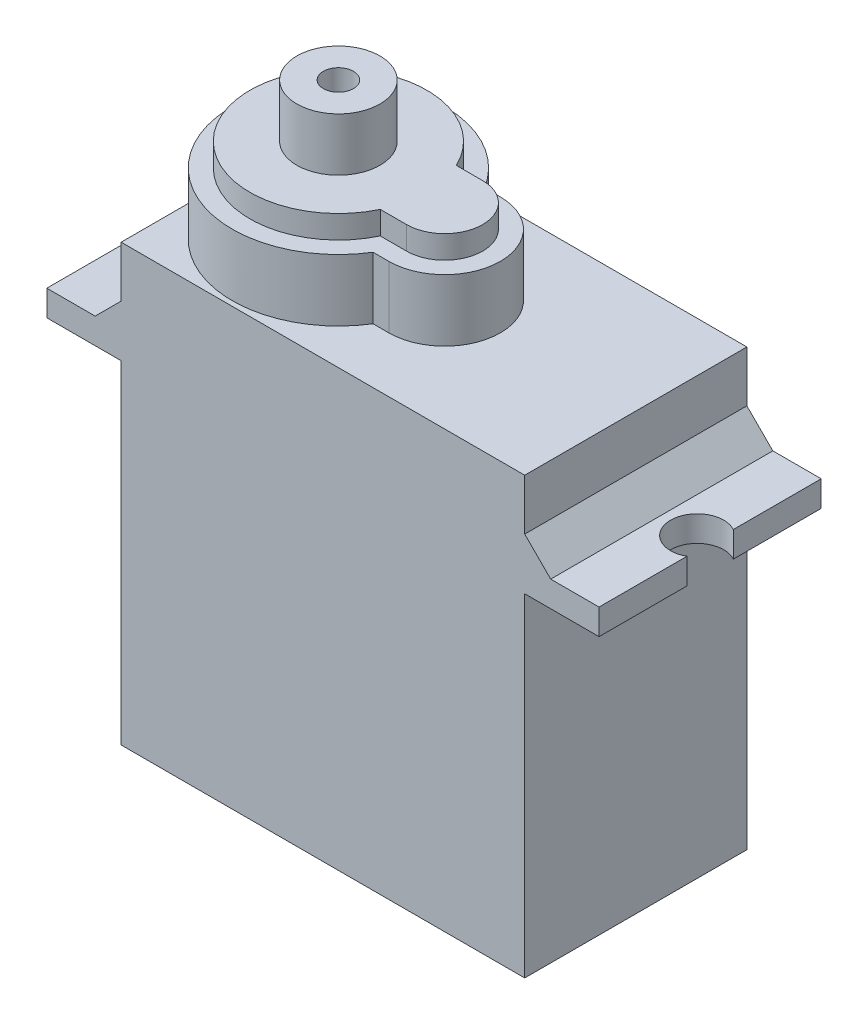
SolidWorks part; units mm, degrees
ref_plane "Piano frontale" through (0, 0, 0) normal (0, 0, 1) x (1, 0, 0)
ref_plane "Piano superiore" through (0, 0, 0) normal (0, 1, 0) x (1, 0, 0)
ref_plane "Piano destro" through (0, 0, 0) normal (1, 0, 0) x (0, 0, -1)
sketch "Schizzo1" plane through (0, 0, 0) normal (0, 0, 1) x (1, 0, 0)
  line L0 (11.4, 21.7179) -> (12.8679, 20.25)
  line L2 (-11.4, 18.8) -> (-11.4, 0)
  line L3 (-11.4, 0) -> (11.4, 0)
  line L4 (11.4, 18.8) -> (11.4, 0)
  line L5 (-15.6, 20.25) -> (-12.8679, 20.25)
  line L6 (-15.6, 20.25) -> (-15.6, 18.8)
  line L7 (-15.6, 18.8) -> (-11.4, 18.8)
  line L8 (15.6, 20.25) -> (15.6, 18.8)
  line L9 (-11.4, 24.6) -> (11.4, 24.6)
  line L10 (-11.4, 24.6) -> (-11.4, 21.7179)
  line L12 (11.4, 24.6) -> (11.4, 21.7179)
  line L13 (12.8679, 20.25) -> (15.6, 20.25)
  line L14 (-11.4, 21.7179) -> (-12.8679, 20.25)
  line L15 (11.4, 18.8) -> (15.6, 18.8)
  dimension "D1" = 18.8
  dimension "D2" = 22.8
  dimension "D3" = 31.2
  dimension "D4" = 1.45
extrude "Estrusione-Estrusione2" add sketch "Schizzo1" along normal blind 12.55
sketch "Schizzo2" plane through (0, 24.6, 0) normal (0, 1, 0) x (1, 0, 0)
  line L0 (-11.4, -12.55) -> (-11.4, 0) construction
  line L1 (0.6, -3.125) -> (-0.2934, -3.125)
  line L2 (0.6, -9.425) -> (-0.2934, -9.425)
  arc A0 (-0.2934, -3.125) -> (-0.2934, -9.425) centre (-5.4, -6.275) ccw
  arc A1 (0.6, -9.425) -> (0.6, -3.125) centre (0.6, -6.275) ccw
  point P2 (-11.4, -6.275)
  dimension "D1" = 12
  dimension "D2" = 6.3
  dimension "D3" = 6
extrude "Estrusione-Estrusione3" add sketch "Schizzo2" along normal blind 3.5
sketch "Schizzo3" plane through (0, 28.1, 0) normal (0, 1, 0) x (1, 0, 0)
  line L0 (-0.8859, -8.425) -> (0.6, -8.425)
  line L1 (0.6, -4.125) -> (-0.8859, -4.125)
  line L2 (-0.2934, -9.425) -> (0.6, -9.425)
  line L3 (0.6, -3.125) -> (-0.2934, -3.125)
  line L4 (-0.2934, -9.425) -> (0.6, -9.425)
  line L5 (0.6, -3.125) -> (-0.2934, -3.125)
  arc A0 (-0.8859, -4.125) -> (-0.8859, -8.425) centre (-5.4, -6.275) ccw
  arc A1 (0.6, -8.425) -> (0.6, -4.125) centre (0.6, -6.275) ccw
  arc A2 (-0.2934, -3.125) -> (-0.2934, -9.425) centre (-5.4, -6.275) ccw
  arc A3 (0.6, -9.425) -> (0.6, -3.125) centre (0.6, -6.275) ccw
  arc A4 (-0.2934, -3.125) -> (-0.2934, -9.425) centre (-5.4, -6.275) ccw
  arc A5 (0.6, -9.425) -> (0.6, -3.125) centre (0.6, -6.275) ccw
  dimension "D1" = 0
  dimension "D2" = 1
extrude "Estrusione-Estrusione4" add sketch "Schizzo3" along normal blind 1.3 contours L0 A1 L1 A0
sketch "Schizzo4" plane through (0, 29.4, 0) normal (0, 1, 0) x (1, 0, 0)
  circle A0 centre (-5.4, -6.275) radius 2.35
  circle A1 centre (-5.4, -6.275) radius 0.85
  dimension "D1" = 4.7
  dimension "D2" = 1.7
extrude "Estrusione-Estrusione5" add sketch "Schizzo4" along normal blind 3
sketch "Schizzo6" plane through (0, 20.25, 0) normal (0, 1, 0) x (1, 0, 0)
  line L0 (-12.8679, -12.55) -> (-12.8679, 0) construction
  line L1 (0, 3.1953) -> (0, -14.2648) construction
  circle A0 centre (-14.8679, -6.275) radius 1.5
  circle A1 centre (14.8679, -6.275) radius 1.5
  point P2 (-12.8679, -6.275)
  dimension "D1" = 3
extrude "Taglio-Estrusione1" cut sketch "Schizzo6" against normal up to next
